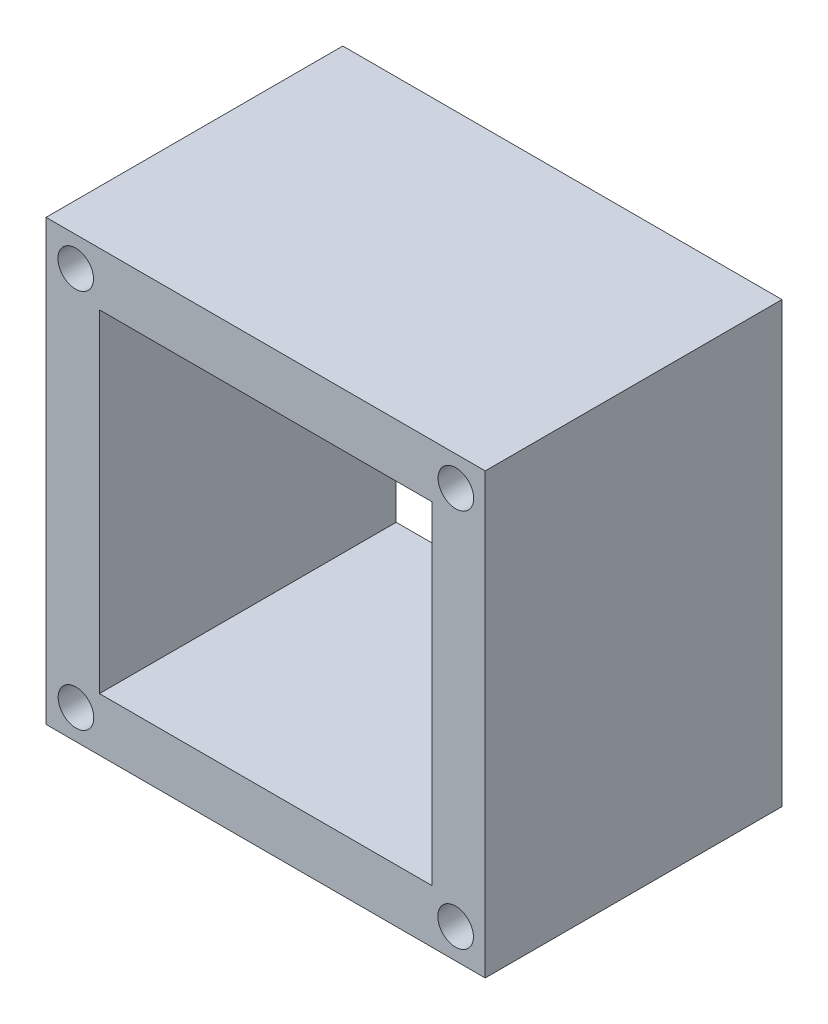
SolidWorks part; units mm, degrees
ref_plane "Front Plane" through (0, 0, 0) normal (0, 0, 1) x (1, 0, 0)
ref_plane "Top Plane" through (0, 0, 0) normal (0, 1, 0) x (1, 0, 0)
ref_plane "Right Plane" through (0, 0, 0) normal (1, 0, 0) x (0, 0, -1)
sketch "Sketch1" plane through (0, 0, 0) normal (0, 0, 1) x (1, 0, 0)
  line L1 (-18.5, 18.5) -> (18.5, 18.5)
  line L2 (-18.5, 18.5) -> (-18.5, -18.5)
  line L3 (-18.5, -18.5) -> (18.5, -18.5)
  line L4 (18.5, 18.5) -> (18.5, -18.5)
  line L5 (-18.5, 18.5) -> (18.5, -18.5) construction
  line L6 (-18.5, -18.5) -> (18.5, 18.5) construction
  point P0 (0, 0)
  dimension "D1" = 37
  dimension "D2" = 37
extrude "Boss-Extrude1" add sketch "Sketch1" along normal blind 25 contours L1 L4 L3 L2
sketch "Sketch2" plane through (0, 0, 25) normal (0, 0, 1) x (1, 0, 0)
  line L1 (-14, 14) -> (14, 14)
  line L2 (-14, 14) -> (-14, -14)
  line L3 (-14, -14) -> (14, -14)
  line L4 (14, 14) -> (14, -14)
  line L5 (-14, 14) -> (14, -14) construction
  line L6 (-14, -14) -> (14, 14) construction
  point P0 (0, 0)
  dimension "D1" = 28
  dimension "D2" = 28
extrude "Cut-Extrude1" cut sketch "Sketch2" against normal through all
sketch "Sketch4" plane through (0, 0, 25) normal (0, 0, 1) x (1, 0, 0)
  line L0 (-18.5, 18.5) -> (18.5, -18.5) construction
  line L1 (-18.5, -18.5) -> (18.5, 18.5) construction
  point P8 (-16.0039, 16.0039)
  point P9 (16.0039, 16.0039)
  point P10 (16.0039, -16.0039)
  point P11 (-16.0039, -16.0039)
  dimension "D1" = 3.53
  dimension "D2" = 3.53
  dimension "D3" = 3.53
  dimension "D4" = 3.53
sketch "Sketch6" plane through (0, 0, 25) normal (0, 0, 1) x (1, 0, 0)
  circle A0 centre (-16.0039, 16.0039) radius 1.5
  circle A1 centre (16.0273, 15.9947) radius 1.5
  circle A2 centre (16.0035, -15.9979) radius 1.5
  circle A3 centre (-15.9788, -16.0039) radius 1.5
  dimension "D1" = 3
extrude "Cut-Extrude3" cut sketch "Sketch6" against normal through all
